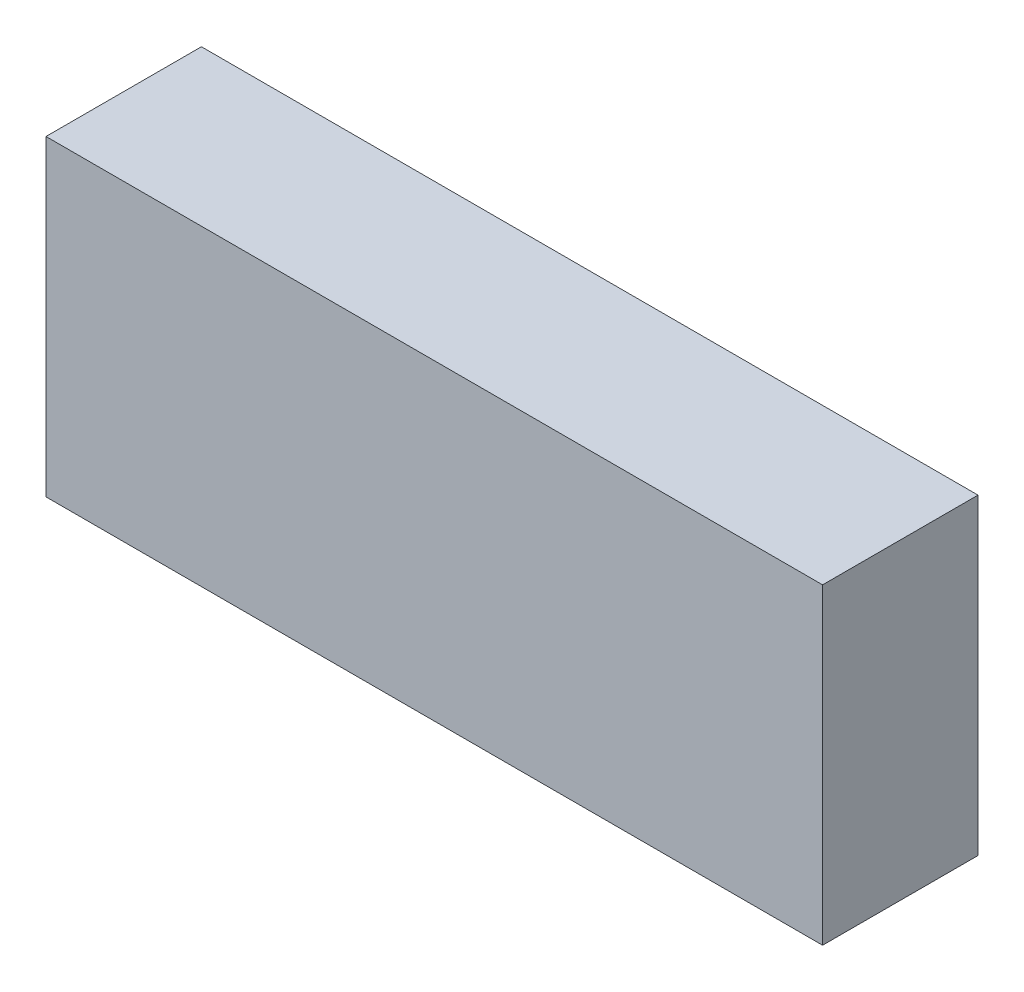
SolidWorks part; units mm, degrees
ref_plane "Front Plane" through (0, 0, 0) normal (0, 0, 1) x (1, 0, 0)
ref_plane "Top Plane" through (0, 0, 0) normal (0, 1, 0) x (1, 0, 0)
ref_plane "Right Plane" through (0, 0, 0) normal (1, 0, 0) x (0, 0, -1)
sketch "Sketch1" plane through (0, 0, 0) normal (0, 0, 1) x (1, 0, 0)
  line L0 (-2.4984, 1.0084) -> (2.4984, 1.0084)
  line L1 (2.4984, 1.0084) -> (2.4984, -1)
  line L2 (2.4984, -1) -> (-2.4984, -1)
  line L3 (-2.4984, -1) -> (-2.4984, 1.0084)
extrude "Component_Outline" add sketch "Sketch1" along normal blind 1 separate body
sketch3d "3DSketch1"
  line L0 (0, 0, 0) -> (1, 0, 0)
  line L1 (0, 0, 0) -> (0, 1, 0)
  line L2 (0, 0, 0) -> (0, 0, 1)
  point P0 (0, 0, 0)
